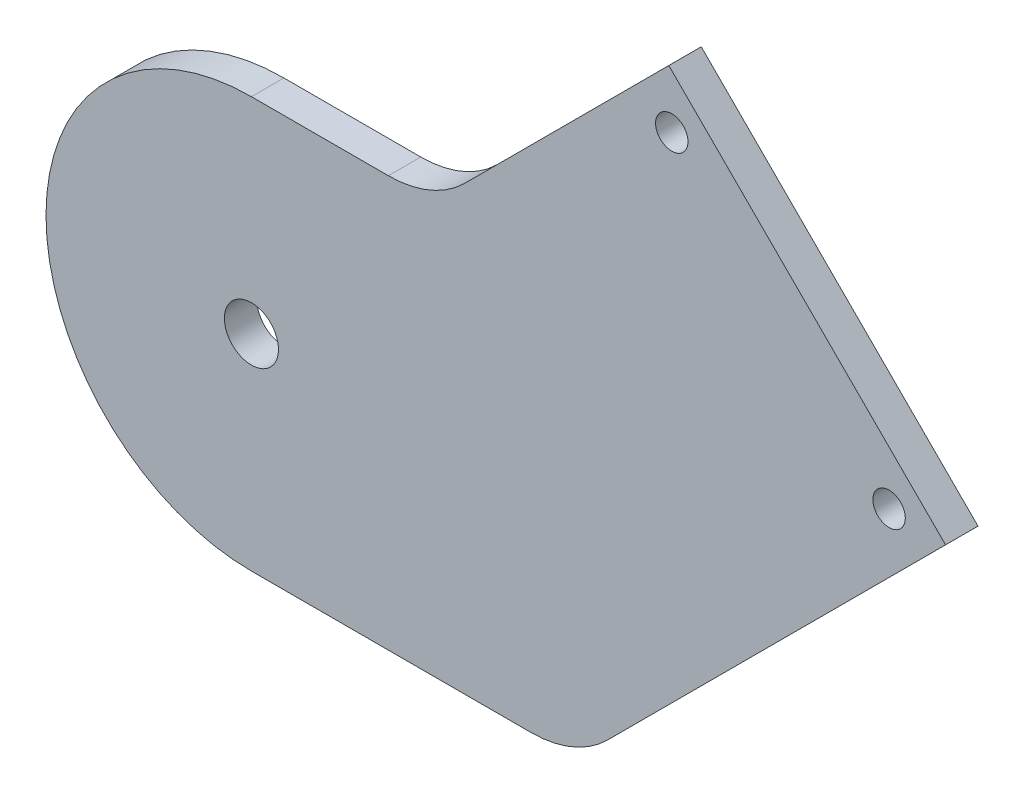
SolidWorks part; units mm, degrees
material "Acrylic (Medium-high impact)"
ref_plane "Front Plane" through (0, 0, 0) normal (0, 0, 1) x (1, 0, 0)
ref_plane "Top Plane" through (0, 0, 0) normal (0, 1, 0) x (1, 0, 0)
ref_plane "Right Plane" through (0, 0, 0) normal (1, 0, 0) x (0, 0, -1)
sketch "Sketch1" plane through (0, 0, 0) normal (0, 0, 1) x (1, 0, 0)
  line L0 (51.4027, 28) -> (24.5327, 1.1299) construction
  line L1 (0, -19) -> (30, -19)
  line L2 (17.3202, 8.3424) -> (31.7452, -6.0825) construction
  line L3 (31.7452, -6.0825) -> (58.6152, 20.7875) construction
  line L4 (17.3202, 8.3424) -> (44.1902, 35.2125) construction
  line L5 (30, -19) -> (64.2014, 15.2014)
  line L6 (44.1902, 35.2125) -> (58.6152, 20.7875)
  line L7 (64.2014, 15.2014) -> (58.6152, 20.7875)
  line L8 (0, 0) -> (0, 28) construction
  line L9 (44.1902, 35.2125) -> (38.6041, 40.7986)
  line L10 (38.6041, 40.7986) -> (16.8055, 19)
  line L11 (16.8055, 19) -> (0, 19)
  line L12 (0, 0) -> (-19, 0) construction
  line L19 (51.4027, 28) -> (0, 28) construction
  arc A0 (0, 19) -> (0, -19) centre (0, 0) ccw
  circle A1 centre (0, 0) radius 2.5
  dimension "D1" = 38
  dimension "D5" = 30
  dimension "D6" = 5
  dimension "D14" = 45
  dimension "D2" = 20.4
  dimension "D3" = 38
  dimension "D4" = 36.2
  dimension "D13" = 28
extrude "Boss-Extrude1" add sketch "Sketch1" along normal blind 3
sketch "Sketch2" plane through (0, 0, 3) normal (0, 0, 1) x (1, 0, 0)
  line L0 (51.4027, 28) -> (31.4988, 8.0961) construction
  line L1 (64.2014, 15.2014) -> (38.6041, 40.7986) construction
  circle A0 centre (38.8781, 35.5749) radius 1.5
  circle A1 centre (58.9776, 15.4754) radius 1.5
  dimension "D1" = 3
  dimension "D2" = 3.5
  dimension "D3" = 28.425
extrude "Cut-Extrude1" cut sketch "Sketch2" against normal through all
fillet "Fillet1" radius 10 2 edges at (16.8055, 19, 1.5) (30, -19, 1.5)
equation "\"D2@Sketch1\"=20.20mm+\"cut_free@Parameters@Parameters.SLDPRT\""
